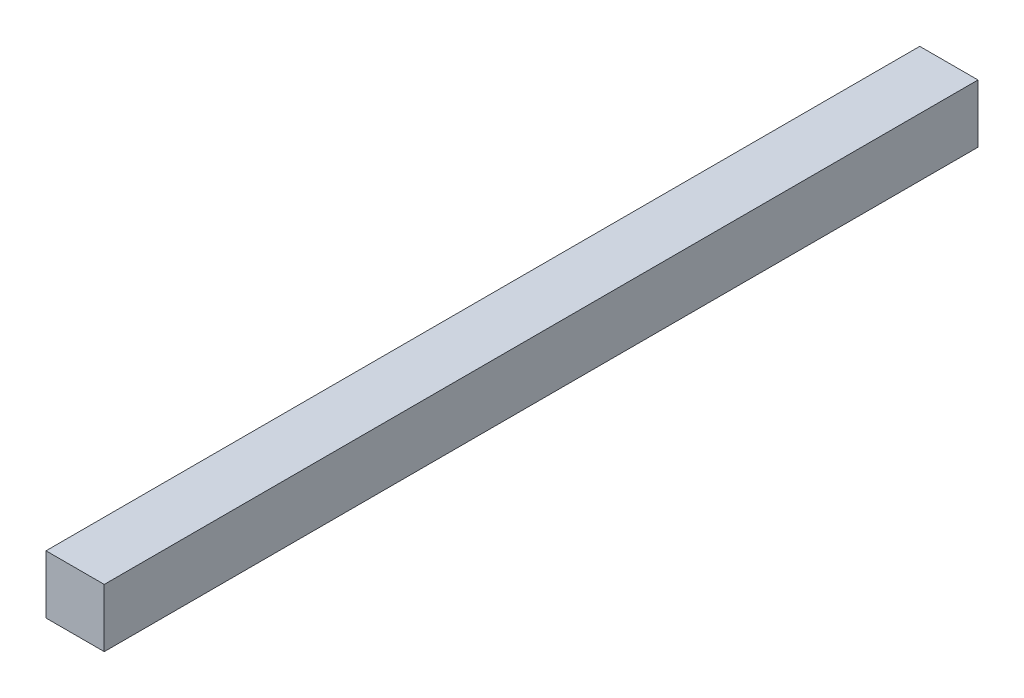
SolidWorks part; units mm, degrees
ref_plane "Front Plane" through (0, 0, 0) normal (0, 0, 1) x (1, 0, 0)
ref_plane "Top Plane" through (0, 0, 0) normal (0, 1, 0) x (1, 0, 0)
ref_plane "Right Plane" through (0, 0, 0) normal (1, 0, 0) x (0, 0, -1)
other "Configuration Table"
sketch "Sketch2" plane through (0, 0, 0) normal (0, 0, 1) x (1, 0, 0)
  line L1 (0, 0) -> (100, 0)
  line L2 (0, 0) -> (0, 100)
  line L3 (0, 100) -> (100, 100)
  line L4 (100, 0) -> (100, 100)
  dimension "D1" = 100
  dimension "D2" = 100
extrude "Boss-Extrude1" add sketch "Sketch2" along normal blind 1500
sketch "Sketch3" plane through (0, 0, 0) normal (0, -1, 0) x (1, 0, 0)
  line L0 (0, 1500) -> (100, 1500) construction
  line L1 (100, 1500) -> (100, 0) construction
  circle A0 centre (55, 1455) radius 25
  dimension "D1" = 50
  dimension "D2" = 45
  dimension "D3" = 45
extrude "Cut-Extrude1" [suppressed] cut sketch "Sketch3" against normal up to next
